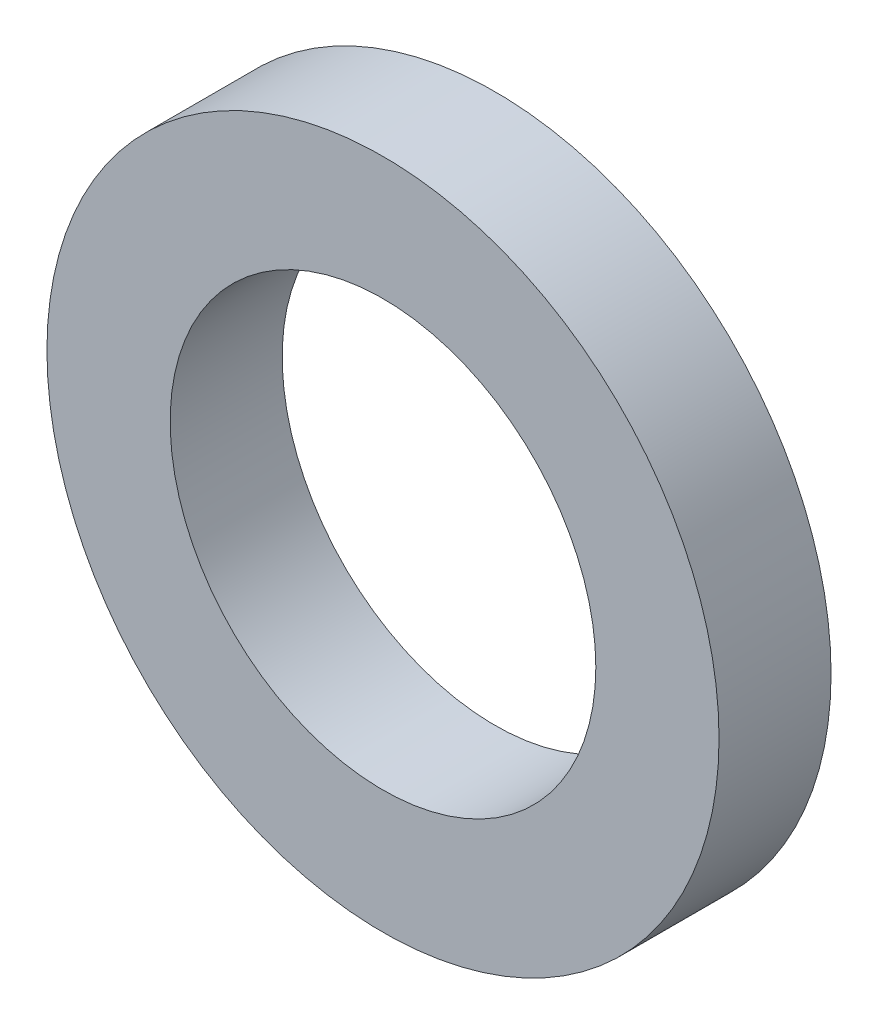
SolidWorks part; units mm, degrees
ref_plane "Front Plane" through (0, 0, 0) normal (0, 0, 1) x (1, 0, 0)
ref_plane "Top Plane" through (0, 0, 0) normal (0, 1, 0) x (1, 0, 0)
ref_plane "Right Plane" through (0, 0, 0) normal (1, 0, 0) x (0, 0, -1)
sketch "Sketch1" plane through (0, 0, 0) normal (0, 0, 1) x (1, 0, 0)
  circle A0 centre (0, 0) radius 3
  circle A1 centre (0, 0) radius 1.9
extrude "Boss-Extrude1" add sketch "Sketch1" along normal blind 1
